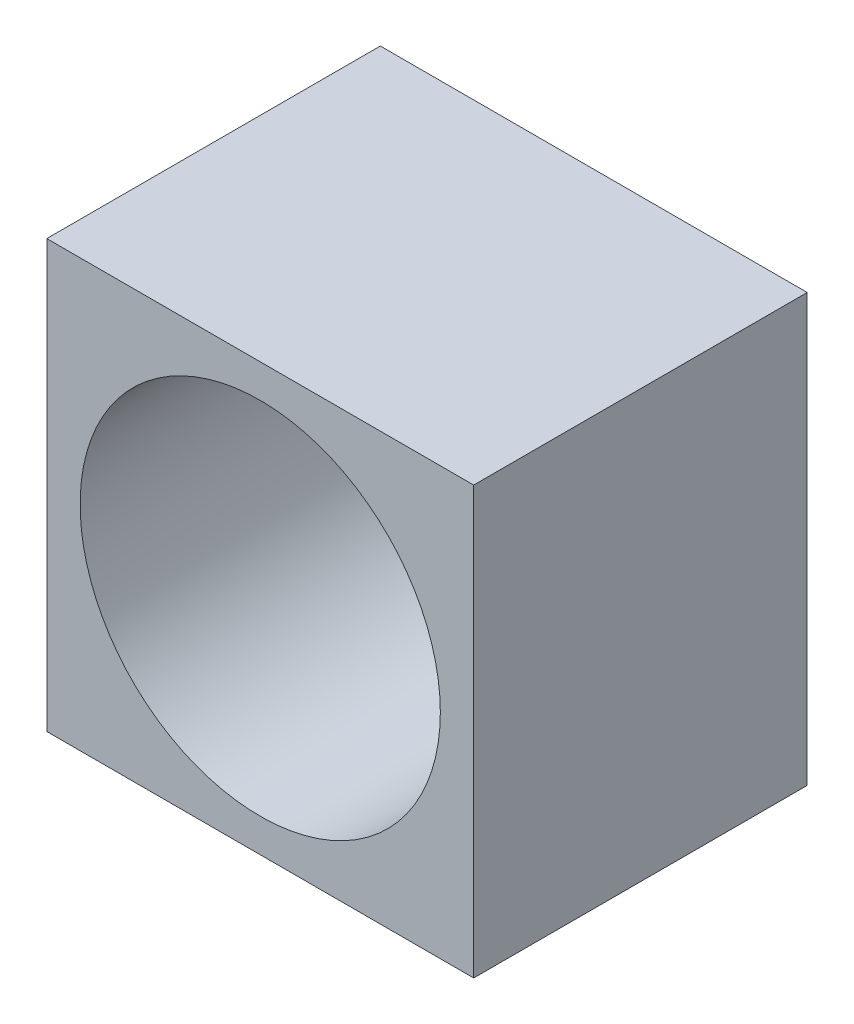
SolidWorks part; units mm, degrees
ref_plane "Спереди" through (0, 0, 0) normal (0, 0, 1) x (1, 0, 0)
ref_plane "Сверху" through (0, 0, 0) normal (0, 1, 0) x (1, 0, 0)
ref_plane "Справа" through (0, 0, 0) normal (1, 0, 0) x (0, 0, -1)
sketch "Эскиз1" plane through (0, 0, 0) normal (0, 0, 1) x (1, 0, 0)
  line L1 (-16, 16) -> (16, 16)
  line L2 (-16, 16) -> (-16, -16)
  line L3 (-16, -16) -> (16, -16)
  line L4 (16, 16) -> (16, -16)
  line L5 (-16, 16) -> (16, -16) construction
  line L6 (-16, -16) -> (16, 16) construction
  point P0 (0, 0)
  dimension "D1" = 32
  dimension "D2" = 32
extrude "Бобышка-Вытянуть1" add sketch "Эскиз1" along normal blind 25
sketch "Эскиз2" plane through (0, 0, 25) normal (0, 0, 1) x (1, 0, 0)
  circle A0 centre (0, 0) radius 13.5
  dimension "D1" = 27
extrude "Вырез-Вытянуть1" cut sketch "Эскиз2" against normal through all
